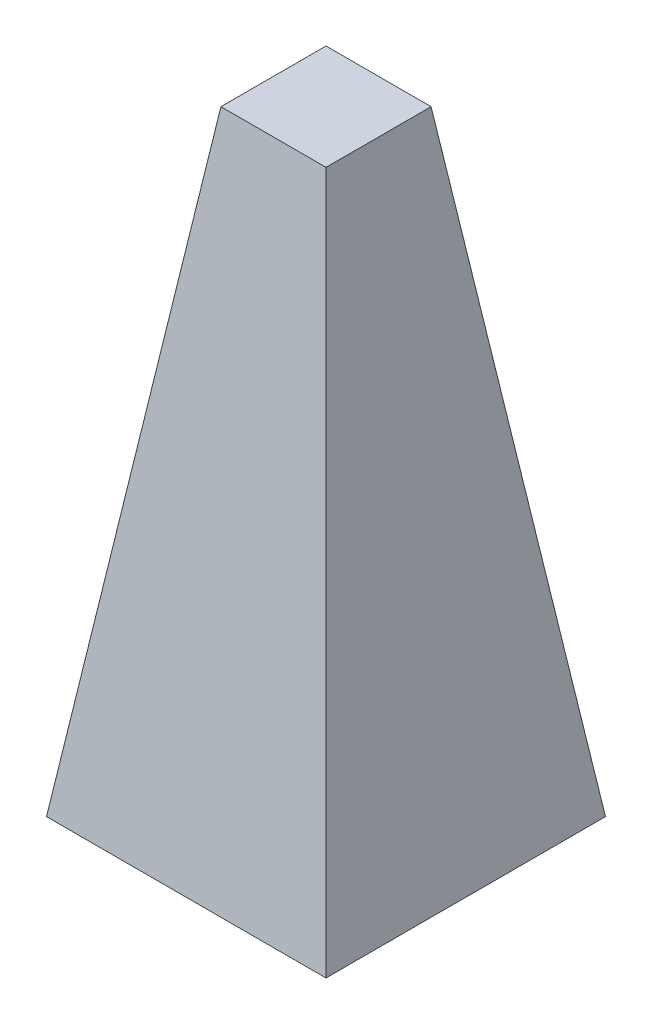
SolidWorks part; units mm, degrees
ref_plane "Front Plane" through (0, 0, 0) normal (0, 0, 1) x (1, 0, 0)
ref_plane "Top Plane" through (0, 0, 0) normal (0, 1, 0) x (1, 0, 0)
ref_plane "Right Plane" through (0, 0, 0) normal (1, 0, 0) x (0, 0, -1)
sketch "Sketch1" plane through (0, 0, 0) normal (0, 1, 0) x (1, 0, 0)
  line L1 (-63.5, -63.5) -> (63.5, -63.5)
  line L2 (-63.5, -63.5) -> (-63.5, 63.5)
  line L3 (-63.5, 63.5) -> (63.5, 63.5)
  line L4 (63.5, -63.5) -> (63.5, 63.5)
  line L5 (-63.5, -63.5) -> (63.5, 63.5) construction
  line L6 (-63.5, 63.5) -> (63.5, -63.5) construction
  point P0 (0, 0)
  dimension "D1" = 127
ref_plane "Plane1" through (0, 279.4, 0) normal (0, 1, 0) x (1, 0, 0)
sketch "Sketch2" plane through (0, 279.4, 0) normal (0, 1, 0) x (1, 0, 0)
  line L1 (-23.876, -23.876) -> (23.876, -23.876)
  line L2 (-23.876, -23.876) -> (-23.876, 23.876)
  line L3 (-23.876, 23.876) -> (23.876, 23.876)
  line L4 (23.876, -23.876) -> (23.876, 23.876)
  line L5 (-23.876, -23.876) -> (23.876, 23.876) construction
  line L6 (-23.876, 23.876) -> (23.876, -23.876) construction
  point P0 (0, 0)
  dimension "D1" = 47.752
loft "Loft1" add profiles "Sketch1", "Sketch2"
